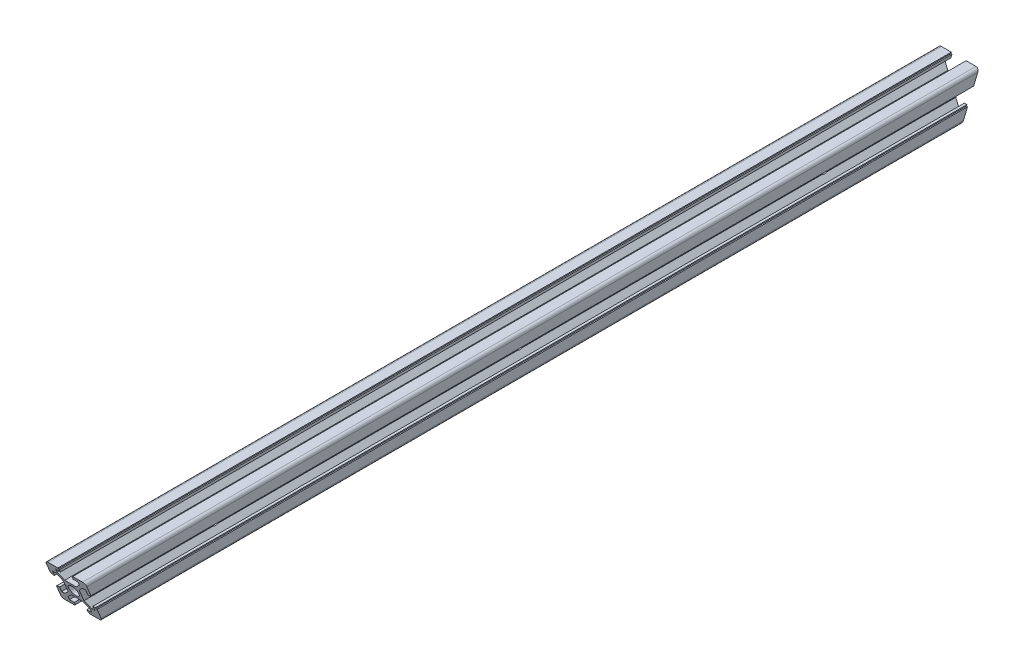
SolidWorks part; units mm, degrees
material "6063-T5"
ref_plane "前视基准面" through (0, 0, 0) normal (0, 0, 1) x (1, 0, 0)
ref_plane "上视基准面" through (0, 0, 0) normal (0, 1, 0) x (1, 0, 0)
ref_plane "右视基准面" through (0, 0, 0) normal (1, 0, 0) x (0, 0, -1)
sketch "草图2" plane through (0, 0, 0) normal (0, 0, 1) x (1, 0, 0)
  line L0 (-3.9, 2.8393) -> (-6.5607, 5.5)
  line L1 (-2.8393, 3.9) -> (2.8393, 3.9)
  line L2 (-3.9, 2.8393) -> (-3.9, -2.8393)
  line L3 (-2.8393, -3.9) -> (2.8393, -3.9)
  line L4 (3.9, 2.8393) -> (3.9, -2.8393)
  line L5 (-3.9, 3.9) -> (3.9, -3.9) construction
  line L6 (-3.9, -3.9) -> (3.9, 3.9) construction
  line L7 (-2.8393, 3.9) -> (-5.5, 6.5607)
  line L8 (-5.5, 6.5607) -> (-5.5, 8.2)
  line L9 (-5.5, 8.2) -> (-3.1, 8.2)
  line L10 (-3.1, 8.2) -> (-3.1, 9.45)
  line L11 (-3.1, 9.45) -> (-3.65, 9.45)
  line L12 (-3.65, 9.45) -> (-3.65, 10)
  line L13 (-3.65, 10) -> (-8.5, 10)
  line L14 (-6.5607, 5.5) -> (-8.2, 5.5)
  line L15 (-10, 3.65) -> (-10, 8.5)
  line L16 (-9.45, 3.65) -> (-10, 3.65)
  line L17 (-9.45, 3.1) -> (-9.45, 3.65)
  line L18 (-8.2, 3.1) -> (-9.45, 3.1)
  line L19 (-8.2, 5.5) -> (-8.2, 3.1)
  line L20 (2.8393, 3.9) -> (5.5, 6.5607)
  line L21 (3.9, 2.8393) -> (6.5607, 5.5)
  line L22 (6.5607, 5.5) -> (8.2, 5.5)
  line L23 (8.2, 5.5) -> (8.2, 3.1)
  line L24 (8.2, 3.1) -> (9.45, 3.1)
  line L25 (9.45, 3.1) -> (9.45, 3.65)
  line L26 (9.45, 3.65) -> (10, 3.65)
  line L27 (10, 3.65) -> (10, 8.5)
  line L28 (5.5, 6.5607) -> (5.5, 8.2)
  line L29 (3.65, 10) -> (8.5, 10)
  line L30 (3.65, 9.45) -> (3.65, 10)
  line L31 (3.1, 9.45) -> (3.65, 9.45)
  line L32 (3.1, 8.2) -> (3.1, 9.45)
  line L33 (5.5, 8.2) -> (3.1, 8.2)
  line L34 (3.9, -2.8393) -> (6.5607, -5.5)
  line L35 (2.8393, -3.9) -> (5.5, -6.5607)
  line L36 (5.5, -6.5607) -> (5.5, -8.2)
  line L37 (5.5, -8.2) -> (3.1, -8.2)
  line L38 (3.1, -8.2) -> (3.1, -9.45)
  line L39 (3.1, -9.45) -> (3.65, -9.45)
  line L40 (3.65, -9.45) -> (3.65, -10)
  line L41 (3.65, -10) -> (8.5, -10)
  line L42 (6.5607, -5.5) -> (8.2, -5.5)
  line L43 (10, -3.65) -> (10, -8.5)
  line L44 (9.45, -3.65) -> (10, -3.65)
  line L45 (9.45, -3.1) -> (9.45, -3.65)
  line L46 (8.2, -3.1) -> (9.45, -3.1)
  line L47 (8.2, -5.5) -> (8.2, -3.1)
  line L48 (-2.8393, -3.9) -> (-5.5, -6.5607)
  line L49 (-3.9, -2.8393) -> (-6.5607, -5.5)
  line L50 (-6.5607, -5.5) -> (-8.2, -5.5)
  line L51 (-8.2, -5.5) -> (-8.2, -3.1)
  line L52 (-8.2, -3.1) -> (-9.45, -3.1)
  line L53 (-9.45, -3.1) -> (-9.45, -3.65)
  line L54 (-9.45, -3.65) -> (-10, -3.65)
  line L55 (-10, -3.65) -> (-10, -8.5)
  line L56 (-5.5, -6.5607) -> (-5.5, -8.2)
  line L57 (-3.65, -10) -> (-8.5, -10)
  line L58 (-3.65, -9.45) -> (-3.65, -10)
  line L59 (-3.1, -9.45) -> (-3.65, -9.45)
  line L60 (-3.1, -8.2) -> (-3.1, -9.45)
  line L61 (-5.5, -8.2) -> (-3.1, -8.2)
  circle A0 centre (0, 0) radius 2.55
  arc A1 (-8.5, 10) -> (-10, 8.5) centre (-8.5, 8.5) ccw
  arc A2 (10, 8.5) -> (8.5, 10) centre (8.5, 8.5) ccw
  arc A3 (8.5, -10) -> (10, -8.5) centre (8.5, -8.5) ccw
  arc A4 (-10, -8.5) -> (-8.5, -10) centre (-8.5, -8.5) ccw
  point P25 (-10, 10)
  point P79 (0, 0)
  dimension "D1" = 5.1
  dimension "D9" = 1.5
  dimension "D2" = 7.8
  dimension "D3" = 1.5
  dimension "D4" = 10
  dimension "D5" = 3.1
  dimension "D6" = 0.55
  dimension "D7" = 1.8
  dimension "D8" = 5.5
  dimension "D11" = 3.9
  dimension "D10" = 4
extrude "凸台-拉伸1" add sketch "草图2" along normal blind 440
sketch "草图3" plane through (10, 0, 0) normal (1, 0, 0) x (0, 0, -1)
  line L0 (-440, 0) -> (0, 0) construction
  line L1 (-440, -2.8393) -> (-440, 2.8393) construction
  circle A2 centre (-70, 0) radius 3
  circle A3 centre (-370, 0) radius 3
  circle A4 centre (-220, 0) radius 3
  point P11 (-220, 0)
  point P14 (0, 0)
  dimension "D1" = 6
  dimension "D2" = 6
  dimension "D4" = 150
  dimension "D5" = 6
  dimension "D3" = 150
extrude "切除-拉伸1" cut sketch "草图3" against normal through all
ref_plane "基准面1" through (8.5, -10, 440) normal (0, 0, -1) x (-1, 0, 0)
sketch "草图5" plane through (10, 0, 0) normal (1, 0, 0) x (0, 0, -1)
  line L0 (-440, 10) -> (-431.7157, -10)
  line L1 (-440, -10) -> (0, -10) construction
  line L2 (0, 10) -> (-8.2843, -10)
  line L5 (-440, 10) -> (-440, -10)
  line L6 (-440, -10) -> (-431.7157, -10)
  line L7 (0, 10) -> (0, -10)
  line L8 (0, -10) -> (-8.2843, -10)
  dimension "D1" = 112.5
  dimension "D2" = 112.5
extrude "切除-拉伸2" cut sketch "草图5" against normal blind 20
